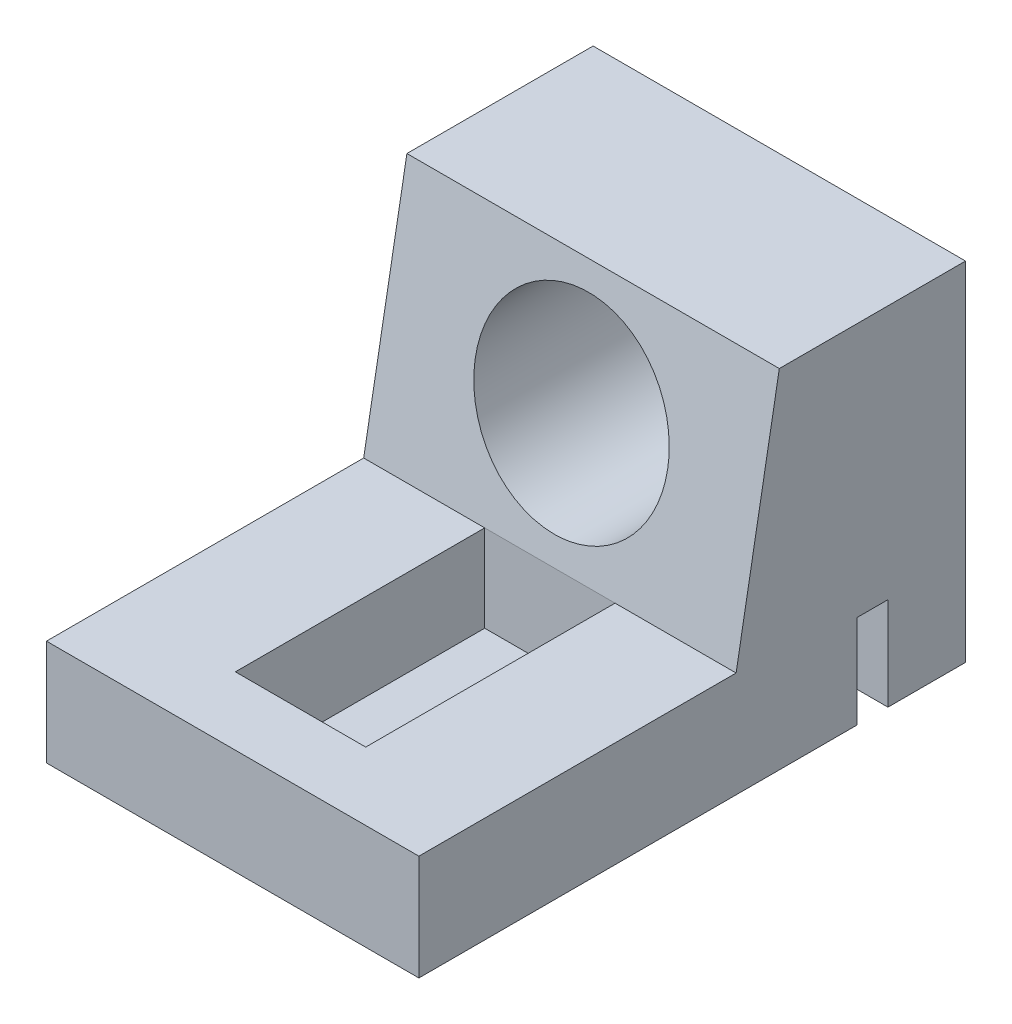
SolidWorks part; units mm, degrees
ref_plane "정면" through (0, 0, 0) normal (0, 0, 1) x (1, 0, 0)
ref_plane "윗면" through (0, 0, 0) normal (0, 1, 0) x (1, 0, 0)
ref_plane "우측면" through (0, 0, 0) normal (1, 0, 0) x (0, 0, -1)
sketch "스케치3" plane through (0, 0, 0) normal (1, 0, 0) x (0, 0, -1)
  line L0 (0, 4.5456) -> (0, -51.4544) construction
  line L1 (-25, -51.4544) -> (25, -51.4544)
  line L2 (-15, 4.5456) -> (15, 4.5456)
  line L3 (-15, 4.5456) -> (-25, -51.4544)
  line L4 (15, 4.5456) -> (25, -51.4544)
  dimension "D2" = 50
  dimension "D3" = 30
  dimension "D4" = 56
extrude "보스-돌출1" add sketch "스케치3" along normal blind 60
sketch "스케치4" plane through (0, 0, 0) normal (0, 0, 1) x (1, 0, 0)
  line L0 (-1.9678, -14.9544) -> (61.9678, -14.9544) construction
  line L1 (30, -51.4544) -> (30, 7.4262) construction
  line L2 (60, -51.4544) -> (0, -51.4544) construction
  circle A0 centre (30, -14.9544) radius 15.5
  dimension "D1" = 31
  dimension "D2" = 21
extrude "컷-돌출1" cut sketch "스케치4" along normal blind 40 and the other way blind 29
sketch "스케치5" plane through (0, 0, 0) normal (1, 0, 0) x (0, 0, -1)
  line L0 (0, 7.2507) -> (0, -19.0866) construction
  line L1 (-25, -51.4544) -> (25, -51.4544) construction
  line L2 (2.5, -66.4544) -> (-2.5, -66.4544)
  line L3 (2.5, -66.4544) -> (2.5, -36.4544)
  line L4 (2.5, -36.4544) -> (-2.5, -36.4544)
  line L5 (-2.5, -66.4544) -> (-2.5, -36.4544)
  line L6 (2.5, -66.4544) -> (-2.5, -36.4544) construction
  line L7 (2.5, -36.4544) -> (-2.5, -66.4544) construction
  point P3 (0, -51.4544)
  dimension "D1" = 5
  dimension "D2" = 30
extrude "컷-돌출2" cut sketch "스케치5" along normal through all
ref_plane "평면1" through (0, -51.4544, 0) normal (0, -1, 0) x (-1, 0, 0)
sketch "스케치7" plane through (0, -51.4544, 0) normal (0, -1, 0) x (-1, 0, 0)
  line L0 (-60, -25) -> (-60, -2.5) construction
  line L1 (-60, -4.5751) -> (0, -4.5751)
  line L2 (-60, -4.5751) -> (-60, -90)
  line L3 (-60, -90) -> (0, -90)
  line L4 (0, -4.5751) -> (0, -90)
  line L5 (-60, -25) -> (0, -25) construction
  dimension "D1" = 65
extrude "보스-돌출2" add sketch "스케치7" against normal blind 17
sketch "스케치9" plane through (0, 0, 0) normal (0, 1, 0) x (1, 0, 0)
  line L0 (30, 25) -> (30, -98.3142) construction
  line L1 (19.5, -21.9643) -> (40.5, -21.9643)
  line L2 (19.5, -21.9643) -> (19.5, -62.1343)
  line L3 (19.5, -62.1343) -> (40.5, -62.1343)
  line L4 (40.5, -21.9643) -> (40.5, -62.1343)
  line L5 (60, 25) -> (0, 25) construction
  line L6 (60, -21.9643) -> (0, -21.9643) construction
  dimension "D1" = 40.17
  dimension "D2" = 10.5
  dimension "D3" = 10.5
extrude "컷-돌출3" cut sketch "스케치9" against normal blind 14 from surface at -34.4544 starting at face at (30, -34.4544, 55.9821)
sketch "스케치12" plane through (0, 0, 0) normal (0, 1, 0) x (1, 0, 0)
  line L0 (0, -90) -> (0, -21.9643) construction
  line L1 (60, -90) -> (0, -90)
  line L2 (60, -90) -> (60, -73.0702)
  line L3 (60, -73.0702) -> (0, -73.0702)
  line L4 (0, -90) -> (0, -73.0702)
extrude "컷-돌출4" cut sketch "스케치12" against normal through all
sketch "스케치14" plane through (0, 0, 0) normal (0, 0, 1) x (1, 0, 0)
  line L0 (-33, -51.4544) -> (33, -51.4544) construction
  line L1 (0, 4.5456) -> (60, 4.5456)
  line L2 (0, 4.5456) -> (0, -51.4544)
  line L3 (0, -51.4544) -> (60, -51.4544)
  line L4 (60, 4.5456) -> (60, -51.4544)
extrude "컷-돌출8" cut sketch "스케치14" against normal blind 10 from offset 15
